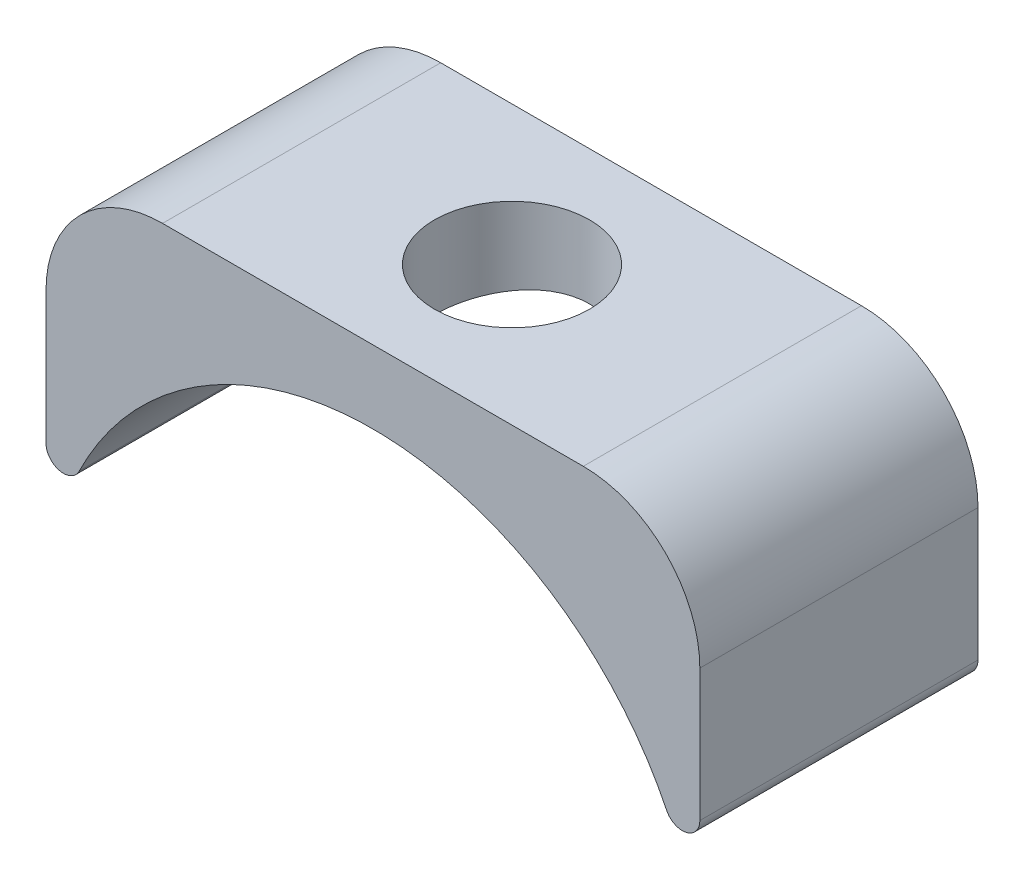
SolidWorks part; units mm, degrees
material "ABS"
ref_plane "X-Y Datum" through (0, 0, 0) normal (0, 0, 1) x (1, 0, 0)
ref_plane "X-Z Datum" through (0, 0, 0) normal (0, 1, 0) x (1, 0, 0)
ref_plane "Y-Z Datum" through (0, 0, 0) normal (1, 0, 0) x (0, 0, -1)
sketch "Sketch2" plane through (0, 0, 0) normal (0, 0, 1) x (1, 0, 0)
  line L0 (-14.25, 6.5904) -> (-14.25, 12.345)
  line L1 (-9.17, 17.425) -> (0, 17.425)
  line L2 (14.25, 12.345) -> (14.25, 6.5904)
  line L6 (0, 17.425) -> (9.17, 17.425)
  line L7 (0, 93.8207) -> (0, -93.8207) construction
  arc A0 (12.8034, 6.2559) -> (0, 14.25) centre (0, 0) ccw
  arc A1 (0, 14.25) -> (-12.8034, 6.2559) centre (0, 0) ccw
  arc A2 (9.17, 17.425) -> (14.25, 12.345) centre (9.17, 12.345) cw
  arc A3 (14.25, 6.5904) -> (12.8034, 6.2559) centre (13.488, 6.5904) cw
  arc A4 (-9.17, 17.425) -> (-14.25, 12.345) centre (-9.17, 12.345) ccw
  arc A5 (-12.8034, 6.2559) -> (-14.25, 6.5904) centre (-13.488, 6.5904) cw
  dimension "D1" = 28.5
  dimension "D2" = 5.08
  dimension "D4" = 0.762
  dimension "D3" = 3.175
extrude "Boss-Extrude1" add sketch "Sketch2" along normal mid plane 12.125
sketch "Sketch3" plane through (0, 0, 0) normal (0, 1, 0) x (1, 0, 0)
  circle A0 centre (0, 0) radius 3.3782
  dimension "D1" = 6.7564
extrude "Cut-Extrude1" cut sketch "Sketch3" against normal through all both and the other way through all
